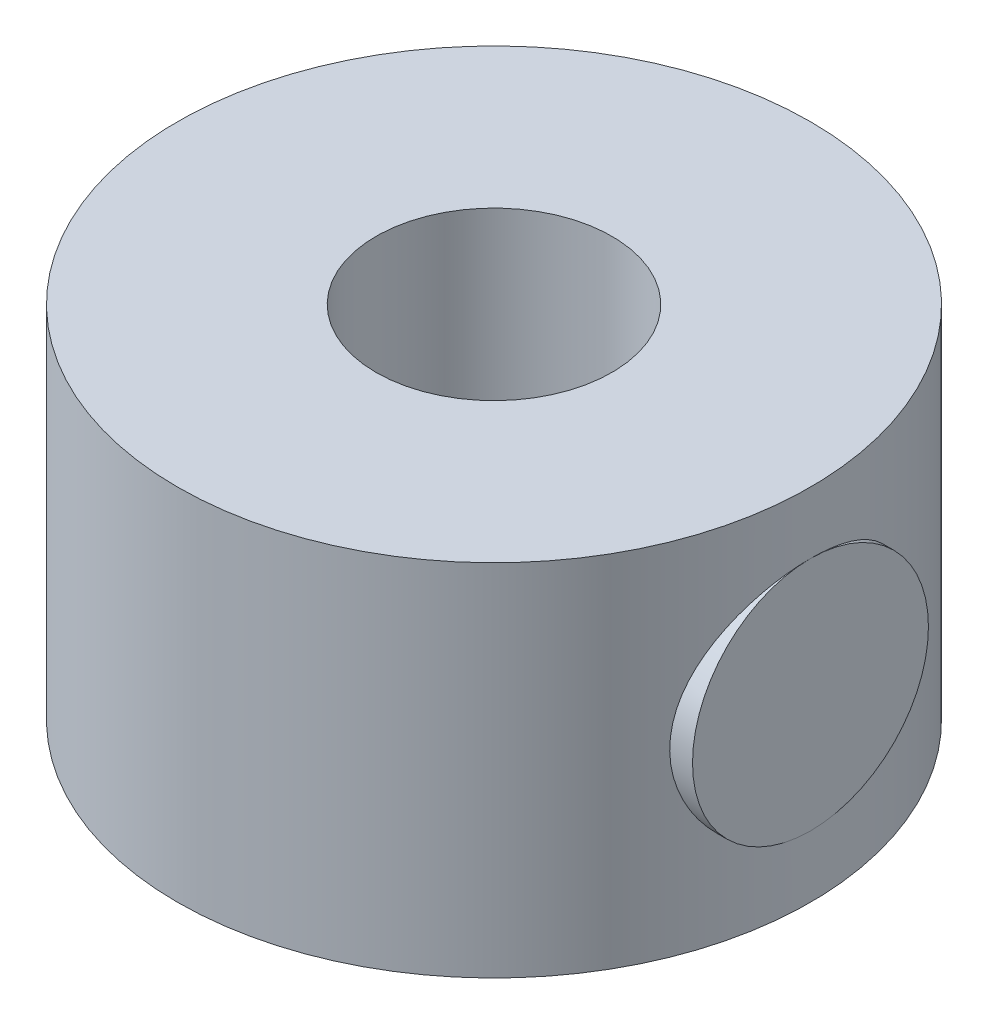
SolidWorks part; units mm, degrees
ref_plane "Front Plane" through (0, 0, 0) normal (0, 0, 1) x (1, 0, 0)
ref_plane "Top Plane" through (0, 0, 0) normal (0, 1, 0) x (1, 0, 0)
ref_plane "Right Plane" through (0, 0, 0) normal (1, 0, 0) x (0, 0, -1)
sketch "Sketch1" plane through (0, 0, 0) normal (0, 1, 0) x (1, 0, 0)
  circle A0 centre (0, 0) radius 5.588
  circle A1 centre (0, 0) radius 2.0828
  dimension "D1" = 11.176
  dimension "D2" = 4.1656
extrude "Boss-Extrude1" add sketch "Sketch1" along normal blind 6.35
ref_plane "Plane1" through (5.588, 0, 0) normal (1, 0, 0) x (0, 0, -1)
sketch "Sketch3" plane through (5.588, 0, 0) normal (1, 0, 0) x (0, 0, -1)
  line L0 (0, 6.35) -> (0, 0) construction
  line L1 (2.0828, 6.35) -> (-2.0828, 6.35) construction
  circle A0 centre (0, 3.175) radius 2.0828
  dimension "D1" = 4.1656
extrude "Boss-Extrude2" add sketch "Sketch3" against normal up to surface (0.4027 mm away)
